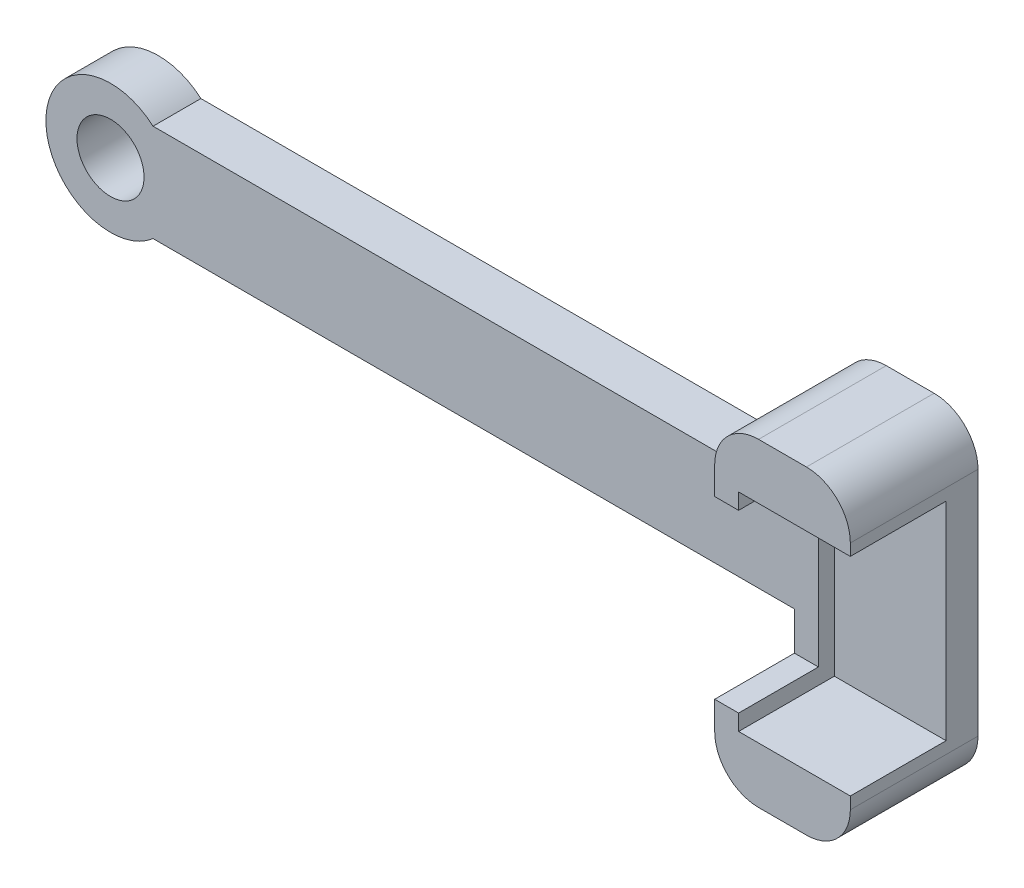
SolidWorks part; units mm, degrees
ref_plane "Alzado" through (0, 0, 0) normal (0, 0, 1) x (1, 0, 0)
ref_plane "Planta" through (0, 0, 0) normal (0, 1, 0) x (1, 0, 0)
ref_plane "Vista lateral" through (0, 0, 0) normal (1, 0, 0) x (0, 0, -1)
sketch "Croquis5" plane through (0, 0, 0) normal (0, 0, 1) x (1, 0, 0)
  line L0 (-12.9124, 50.5821) -> (38.0834, 50.5821)
  line L1 (38.0834, 50.5821) -> (38.0834, 54.8115)
  line L2 (-12.9124, 44.4821) -> (38.0834, 44.4821)
  line L3 (38.0834, 44.4821) -> (38.0834, 40.3321)
  line L4 (46.5834, 40.3321) -> (46.5834, 54.8115)
  line L5 (43.8334, 57.5615) -> (40.8334, 57.5615)
  line L6 (43.8334, 37.5821) -> (40.8334, 37.5821)
  arc A0 (38.0834, 40.3321) -> (40.8334, 37.5821) centre (40.8334, 40.3321) ccw
  arc A1 (43.8334, 37.5821) -> (46.5834, 40.3321) centre (43.8334, 40.3321) ccw
  arc A2 (46.5834, 54.8115) -> (43.8334, 57.5615) centre (43.8334, 54.8115) ccw
  arc A3 (40.8334, 57.5615) -> (38.0834, 54.8115) centre (40.8334, 54.8115) ccw
  circle A4 centre (-15.6666, 47.5321) radius 2.5526
  arc A5 (-12.9124, 50.5821) -> (-12.9124, 44.4821) centre (-15.6666, 47.5321) ccw
  dimension "D1" = 2.75
  dimension "D2" = 14.4794
extrude "Saliente-Extruir4" add sketch "Croquis5" along normal blind 8 separate body
sketch "Croquis6" plane through (0, 0, 8) normal (0, 0, 1) x (1, 0, 0)
  line L0 (-12.9124, 50.5821) -> (38.0834, 50.5821)
  line L1 (38.0834, 50.5821) -> (38.0834, 53.0821)
  line L2 (38.0834, 44.4821) -> (-12.9124, 44.4821)
  line L3 (38.0834, 54.8115) -> (38.0834, 50.5821) construction
  line L4 (38.0834, 53.0821) -> (39.5834, 53.0821)
  line L5 (39.5834, 53.0821) -> (39.5834, 42.0821)
  line L6 (39.5834, 42.0821) -> (38.0834, 42.0821)
  line L8 (38.0834, 42.0821) -> (38.0834, 44.4821)
  circle A0 centre (-15.6666, 47.5321) radius 2.5526
  arc A1 (-12.9124, 50.5821) -> (-12.9124, 44.4821) centre (-15.6666, 47.5321) ccw
  dimension "D1" = 2.5
  dimension "D2" = 1.5
  dimension "D3" = 2.4
extrude "Cortar-Extruir2" cut sketch "Croquis6" against normal blind 5
sketch "Croquis7" plane through (0, 0, 8) normal (0, 0, 1) x (1, 0, 0)
  line L0 (46.5834, 40.3321) -> (46.5834, 54.8115) construction
  line L1 (46.5834, 54.0821) -> (39.5834, 54.0821)
  line L2 (46.5834, 54.0821) -> (46.5834, 41.0821)
  line L3 (46.5834, 41.0821) -> (39.5834, 41.0821)
  line L4 (39.5834, 54.0821) -> (39.5834, 41.0821)
  line L6 (39.5834, 53.0821) -> (38.0834, 53.0821) construction
  dimension "D1" = 7
  dimension "D2" = 13
  dimension "D3" = 1
extrude "Cortar-Extruir3" cut sketch "Croquis7" against normal blind 6
sketch "Croquis8" plane through (0, 0, 0) normal (0, 0, -1) x (-1, 0, 0)
  line L1 (4.7762, 53.194) -> (19.7762, 53.194)
  line L2 (4.7762, 53.194) -> (4.7762, 23.194)
  line L3 (4.7762, 23.194) -> (19.7762, 23.194)
  line L4 (19.7762, 53.194) -> (19.7762, 23.194)
  arc A0 (12.9124, 44.4821) -> (12.9124, 50.5821) centre (15.6666, 47.5321) ccw construction
  point P4 (19.7762, 47.5321)
  dimension "D1" = 0
  dimension "D2" = 30
  dimension "D3" = 15
extrude "Cortar-Extruir4" cut sketch "Croquis8" against normal blind 10
sketch "Croquis9" plane through (0, 0, 0) normal (0, 0, -1) x (-1, 0, 0)
  line L0 (4.7762, 50.5821) -> (4.7762, 44.4821) construction
  circle A0 centre (4.7762, 47.5321) radius 4.05
  dimension "D1" = 8.1
extrude "Saliente-Extruir5" add sketch "Croquis9" against normal blind 3
sketch "Croquis10" plane through (0, 0, 0) normal (0, 0, -1) x (-1, 0, 0)
  circle A0 centre (4.7762, 47.5321) radius 2.1
  dimension "D1" = 4.2
extrude "Cortar-Extruir5" cut sketch "Croquis10" against normal blind 3
